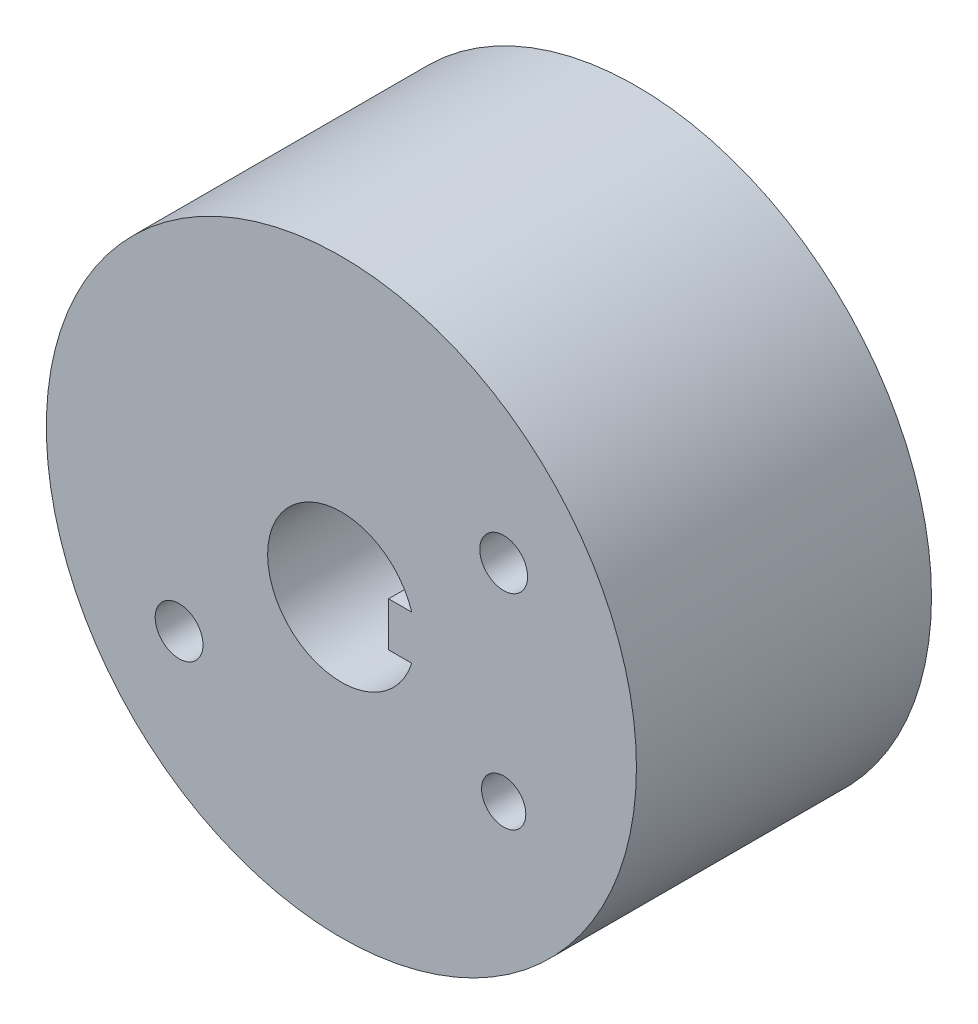
SolidWorks part; units mm, degrees
ref_plane "前视基准面" through (0, 0, 0) normal (0, 0, 1) x (1, 0, 0)
ref_plane "上视基准面" through (0, 0, 0) normal (0, 1, 0) x (1, 0, 0)
ref_plane "右视基准面" through (0, 0, 0) normal (1, 0, 0) x (0, 0, -1)
sketch "草图1" plane through (0, 0, 0) normal (0, 0, 1) x (1, 0, 0)
  circle A0 centre (0, 0) radius 20
  dimension "D1" = 40
extrude "凸台-拉伸1" add sketch "草图1" along normal blind 20
sketch "草图2" plane through (0, 0, 20) normal (0, 0, 1) x (1, 0, 0)
  line L0 (0, 0) -> (8.3901, 0) construction
  line L1 (3.2, -1.5) -> (3.2, 1.5)
  line L2 (3.2, 1.5) -> (4.7697, 1.5)
  line L3 (3.2, -1.5) -> (4.7697, -1.5)
  circle A0 centre (0, 0) radius 5
  point P7 (3.2, 0)
  dimension "D1" = 10
  dimension "D2" = 3.2
  dimension "D3" = 1.5
extrude "切除-拉伸1" cut sketch "草图2" against normal blind 22.5
sketch "草图3" plane through (0, 0, 20) normal (0, 0, 1) x (1, 0, 0)
  line L0 (0, 0) -> (11, 0) construction
  line L1 (11, 0) -> (11, 7.5)
  line L2 (0, 0) -> (-11, 0) construction
  line L3 (-11, 0) -> (-11, 6.5) construction
  line L4 (0, 0) -> (11, 0) construction
  circle A0 centre (0, 0) radius 13.31 construction
  circle A1 centre (11, 7.5) radius 1.62
  circle A2 centre (-11, -7.5) radius 1.62
  circle A3 centre (-11, 6.5) radius 1.5
  circle A4 centre (11, -6.5) radius 1.5
  point P11 (0, 0)
  point P17 (0, 0)
  dimension "D1" = 26.62
  dimension "D4" = 3.24
  dimension "D8" = 3
  dimension "D2" = 11
  dimension "D3" = 7.5
  dimension "D6" = 11
  dimension "D7" = 6.5
  dimension "D5" = 2
  dimension "D9" = 2
extrude "切除-拉伸2" cut sketch "草图3" against normal blind 22.5 contours A4 | A1 | A2
